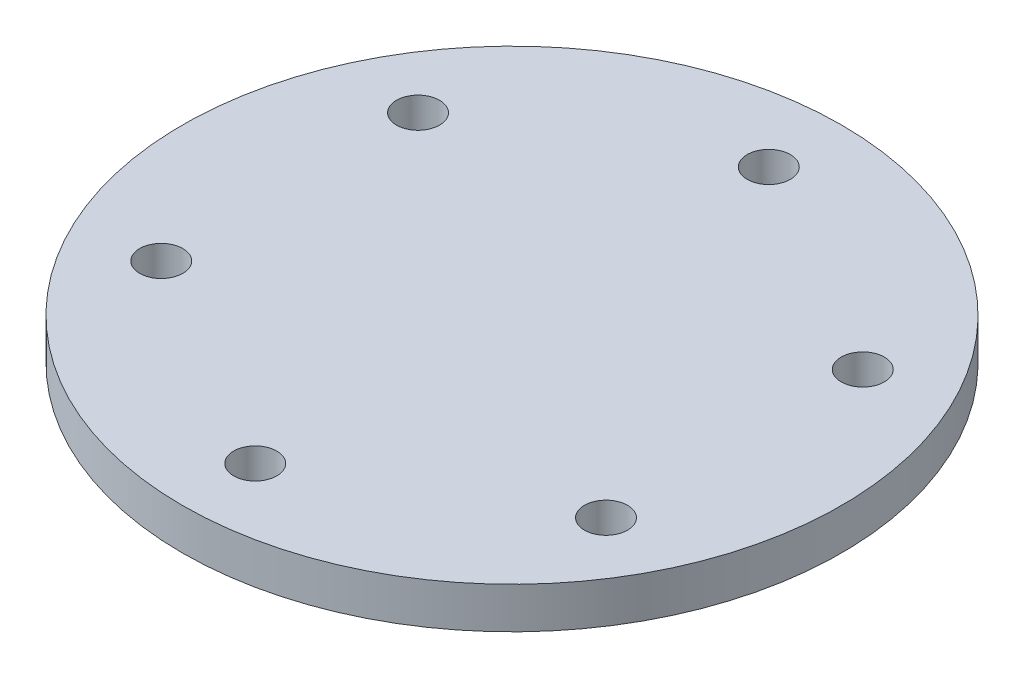
SolidWorks part; units mm, degrees
ref_plane "Front Plane" through (0, 0, 0) normal (0, 0, 1) x (1, 0, 0)
ref_plane "Top Plane" through (0, 0, 0) normal (0, 1, 0) x (1, 0, 0)
ref_plane "Right Plane" through (0, 0, 0) normal (1, 0, 0) x (0, 0, -1)
sketch "Sketch1" plane through (0, 0, 0) normal (0, 1, 0) x (1, 0, 0)
  circle A0 centre (0, 0) radius 30.48
  dimension "D1" = 60.96
extrude "Boss-Extrude1" add sketch "Sketch1" along normal blind 3.81 contours A0
sketch "Sketch2" plane through (0, 3.81, 0) normal (0, 1, 0) x (1, 0, 0)
  line L0 (0, 0) -> (0, -23.749)
  circle A0 centre (0, 0) radius 23.749
  circle A1 centre (0, -23.749) radius 1.9939
  dimension "D1" = 47.498
  dimension "D2" = 3.9878
extrude "Cut-Extrude1" cut sketch "Sketch2" against normal through all contours A1
pattern_circular "CirPattern1" count 6 over 360 about axis through (0, 0, 0) along (0, 1, 0) of "Cut-Extrude1"
sketch "Sketch3" plane through (0, 0, 0) normal (0, -1, 0) x (1, 0, 0)
  line L0 (34.7702, 211.4361) -> (219.4369, 211.4361) construction
  line L1 (33.9001, 212.6029) -> (218.5667, 212.6029) construction
